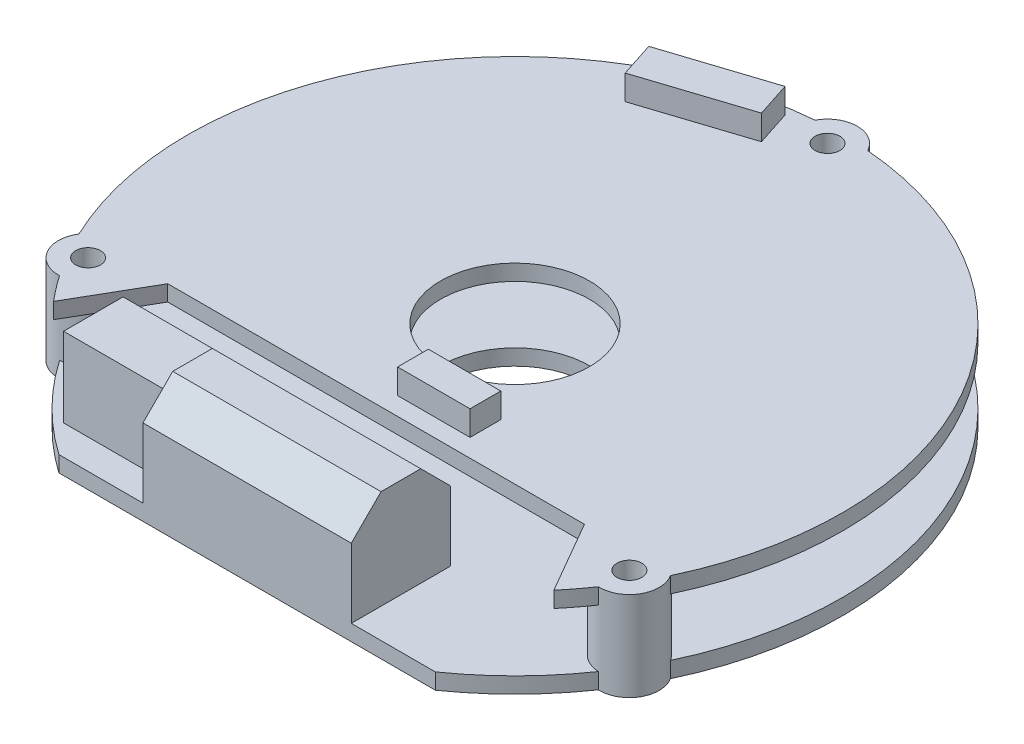
SolidWorks part; units mm, degrees
ref_plane "前视基准面" through (0, 0, 0) normal (0, 0, 1) x (1, 0, 0)
ref_plane "上视基准面" through (0, 0, 0) normal (0, 1, 0) x (1, 0, 0)
ref_plane "右视基准面" through (0, 0, 0) normal (1, 0, 0) x (0, 0, -1)
sketch "草图1" plane through (0, 0, 0) normal (0, 1, 0) x (1, 0, 0)
  line L0 (0, 0) -> (0, 48.7045) construction
  arc A0 (-2.6571, 32.8929) -> (-29.8146, -14.1454) centre (0, 0) ccw
  circle A1 centre (0, 0) radius 7.5
  arc A2 (2.6571, 32.8929) -> (-2.6571, 32.8929) centre (0, 31.5) ccw
  arc A3 (27.1575, -18.7475) -> (29.8146, -14.1454) centre (27.2798, -15.75) ccw
  arc A4 (-29.8146, -14.1454) -> (-27.1575, -18.7475) centre (-27.2798, -15.75) ccw
  arc A5 (-27.1575, -18.7475) -> (27.1575, -18.7475) centre (0, 0) ccw
  arc A6 (29.8146, -14.1454) -> (2.6571, 32.8929) centre (0, 0) ccw
  point P13 (0, 0)
  dimension "D1" = 66
  dimension "D2" = 15
  dimension "D4" = 6
  dimension "D3" = 31.5
  dimension "D5" = 3
extrude "凸台-拉伸1" add sketch "草图1" along normal blind 1.6
sketch "草图4" plane through (0, 1.6, 0) normal (0, 1, 0) x (1, 0, 0)
  circle A0 centre (0, 31.5) radius 3
  circle A1 centre (27.2798, -15.75) radius 3
  circle A2 centre (-27.2798, -15.75) radius 3
  point P9 (0, 0)
  dimension "D1" = 3
extrude "凸台-拉伸2" add sketch "草图4" along normal blind 5.8
sketch "草图6" plane through (0, 7.4, 0) normal (0, 1, 0) x (1, 0, 0)
  line L0 (0, 0) -> (0, -33) construction
  line L1 (-21, -14) -> (21, -14)
  line L2 (-21, -14) -> (-25.2109, -21.2935)
  line L3 (21, -14) -> (25.2109, -21.2935)
  circle A0 centre (0, 0) radius 7.5 construction
  circle A1 centre (0, 31.5) radius 3 construction
  circle A2 centre (27.2798, -15.75) radius 3 construction
  arc A3 (29.8146, -14.1454) -> (2.6571, 32.8929) centre (0, 0) ccw construction
  arc A4 (-27.1575, -18.7475) -> (27.1575, -18.7475) centre (0, 0) ccw construction
  arc A5 (-2.6571, 32.8929) -> (-29.8146, -14.1454) centre (0, 0) ccw construction
  circle A6 centre (-27.2798, -15.75) radius 3 construction
  circle A7 centre (0, 0) radius 7.5
  arc A8 (2.6571, 32.8929) -> (-2.6571, 32.8929) centre (0, 31.5) ccw
  arc A9 (27.1575, -18.7475) -> (29.8146, -14.1454) centre (27.2798, -15.75) ccw
  arc A10 (29.8146, -14.1454) -> (2.6571, 32.8929) centre (0, 0) ccw
  arc A11 (-27.1575, -18.7475) -> (-25.2109, -21.2935) centre (0, 0) ccw
  arc A12 (-2.6571, 32.8929) -> (-29.8146, -14.1454) centre (0, 0) ccw
  arc A13 (-29.8146, -14.1454) -> (-27.1575, -18.7475) centre (-27.2798, -15.75) ccw
  arc A14 (25.2109, -21.2935) -> (27.1575, -18.7475) centre (0, 0) ccw
  point P18 (0, -14)
  dimension "D1" = 14
  dimension "D2" = 42
  dimension "D3" = 120
extrude "凸台-拉伸3" add sketch "草图6" along normal blind 1.6
sketch "草图7" plane through (0, 1.6, 0) normal (0, 1, 0) x (1, 0, 0)
  line L0 (0, 0) -> (0, -33) construction
  line L2 (-10.5, -17) -> (10.5, -17)
  line L3 (-10.5, -17) -> (-10.5, -27)
  line L4 (-10.5, -27) -> (10.5, -27)
  line L5 (10.5, -17) -> (10.5, -27)
  line L6 (-10.5, -17) -> (10.5, -27) construction
  line L7 (-10.5, -27) -> (10.5, -17) construction
  arc A0 (-27.1575, -18.7475) -> (27.1575, -18.7475) centre (0, 0) ccw construction
  point P6 (0, -22)
  dimension "D1" = 21
  dimension "D2" = 10
  dimension "D3" = 22
extrude "凸台-拉伸4" add sketch "草图7" along normal blind 10
chamfer "倒角1" distance 3 angle 45 2 edges at (0, 11.6, 17) (0, 11.6, 27)
sketch "草图8" plane through (0, 1.6, 0) normal (0, 1, 0) x (1, 0, 0)
  line L0 (-10.5, -17) -> (-10.5, -27) construction
  line L1 (-21.5, -18) -> (-11.5, -18)
  line L2 (-21.5, -18) -> (-21.5, -24)
  line L3 (-21.5, -24) -> (-11.5, -24)
  line L4 (-11.5, -18) -> (-11.5, -24)
  line L5 (-21.5, -18) -> (-11.5, -24) construction
  line L6 (-21.5, -24) -> (-11.5, -18) construction
  line L7 (-10.5, -17) -> (10.5, -17) construction
  point P0 (-16.5, -21)
  dimension "D1" = 10
  dimension "D2" = 6
  dimension "D3" = 1
  dimension "D4" = 1
extrude "凸台-拉伸5" add sketch "草图8" along normal blind 8
sketch "草图9" plane through (0, 9, 0) normal (0, 1, 0) x (1, 0, 0)
  line L0 (0, 0) -> (0, -14) construction
  line L1 (-21, -14) -> (21, -14) construction
  line L3 (0.35, -12.1821) -> (7.65, -12.1821)
  line L4 (0.35, -12.1821) -> (0.35, -9.0821)
  line L5 (0.35, -9.0821) -> (7.65, -9.0821)
  line L6 (7.65, -12.1821) -> (7.65, -9.0821)
  line L7 (0.35, -12.1821) -> (7.65, -9.0821) construction
  line L8 (0.35, -9.0821) -> (7.65, -12.1821) construction
  point P5 (4, -10.6321)
  dimension "D1" = 8
  dimension "D2" = 7.3
  dimension "D3" = 3.1
extrude "凸台-拉伸6" add sketch "草图9" along normal blind 2.5
sketch "草图10" plane through (0, 9, 0) normal (0, 1, 0) x (1, 0, 0)
  line L0 (0, 0) -> (0, 34.5) construction
  line L1 (-0.4249, 0) -> (0, 0) construction
  line L2 (0, 0) -> (-11.2397, 34.5922) construction
  line L3 (-13.8357, 24.9454) -> (-3.4692, 28.3137)
  line L8 (-3.4692, 28.3137) -> (-4.6126, 31.8326)
  line L9 (-4.6126, 31.8326) -> (-14.9791, 28.4643)
  line L10 (-14.9791, 28.4643) -> (-13.8357, 24.9454)
  arc A0 (2.6571, 32.8929) -> (-2.6571, 32.8929) centre (0, 31.5) ccw construction
  point P10 (-8.6525, 26.6296)
  dimension "D1" = 18
  dimension "D2" = 28
  dimension "D3" = 10.9
  dimension "D4" = 3.7
extrude "凸台-拉伸7" add sketch "草图10" along normal blind 2.5
sketch "草图11" plane through (0, 9, 0) normal (0, 1, 0) x (1, 0, 0)
  circle A0 centre (0, 31.5) radius 1.25
  circle A1 centre (27.2798, -15.75) radius 1.25
  circle A2 centre (-27.2798, -15.75) radius 1.25
  dimension "D1" = 2.5
  dimension "D2" = 3
extrude "切除-拉伸3" cut sketch "草图11" against normal up to next
sketch "草图12" plane through (0, 1.6, 0) normal (0, 1, 0) x (1, 0, 0)
  line L0 (18.9737, -27) -> (-18.9737, -27)
  arc A0 (-27.1575, -18.7475) -> (27.1575, -18.7475) centre (0, 0) ccw construction
  arc A1 (-18.9737, -27) -> (18.9737, -27) centre (0, 0) ccw
extrude "切除-拉伸4" cut sketch "草图12" against normal up to next
